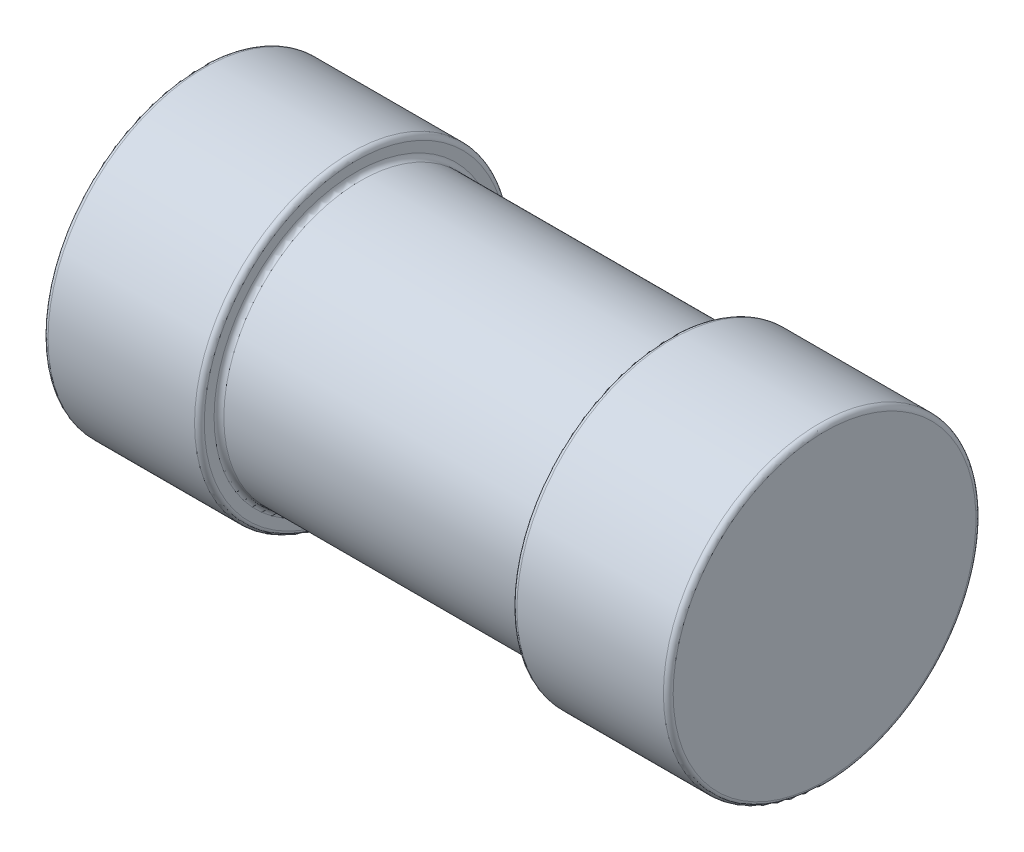
SolidWorks part; units mm, degrees
ref_plane "前视基准面" through (0, 0, 0) normal (0, 0, 1) x (1, 0, 0)
ref_plane "上视基准面" through (0, 0, 0) normal (0, 1, 0) x (1, 0, 0)
ref_plane "右视基准面" through (0, 0, 0) normal (1, 0, 0) x (0, 0, -1)
sketch "草图1" plane through (0, 0, 0) normal (0, 0, 1) x (1, 0, 0)
  line L0 (-2.0683, -4.7685) -> (1.1317, -4.7685) construction
  line L1 (-2.0433, -3.9685) -> (-1.2933, -3.9685)
  line L2 (-2.0683, -3.9935) -> (-2.0683, -4.7685)
  line L3 (-1.2683, -3.9935) -> (-1.2683, -4.0435)
  line L4 (1.1317, -3.9935) -> (1.1317, -4.7685)
  line L5 (-0.4683, -3.9685) -> (-0.4683, -4.7685) construction
  line L6 (0.3317, -3.9935) -> (0.3317, -4.0435)
  line L7 (-1.2433, -4.0685) -> (0.3067, -4.0685)
  line L8 (0.3567, -3.9685) -> (1.1067, -3.9685)
  line L9 (-2.0683, -4.7685) -> (1.1317, -4.7685)
  arc A0 (0.3317, -4.0435) -> (0.3067, -4.0685) centre (0.3067, -4.0435) cw
  arc A1 (-1.2433, -4.0685) -> (-1.2683, -4.0435) centre (-1.2433, -4.0435) cw
  arc A2 (0.3317, -3.9935) -> (0.3567, -3.9685) centre (0.3567, -3.9935) cw
  arc A3 (-1.2683, -3.9935) -> (-1.2933, -3.9685) centre (-1.2933, -3.9935) ccw
  arc A4 (-2.0683, -3.9935) -> (-2.0433, -3.9685) centre (-2.0433, -3.9935) cw
  arc A5 (1.1317, -3.9935) -> (1.1067, -3.9685) centre (1.1067, -3.9935) ccw
  point P16 (0.3317, -3.9685)
  point P19 (-1.2683, -3.9685)
  dimension "D4" = 0.025
  dimension "D5" = 0.025
  dimension "D6" = 0.025
  dimension "D7" = 0.025
  dimension "D8" = 0.025
  dimension "D1" = 3.2
  dimension "D2" = 0.8
  dimension "D3" = 0.1
revolve "旋转3" add sketch "草图1" angle 360 about L9
